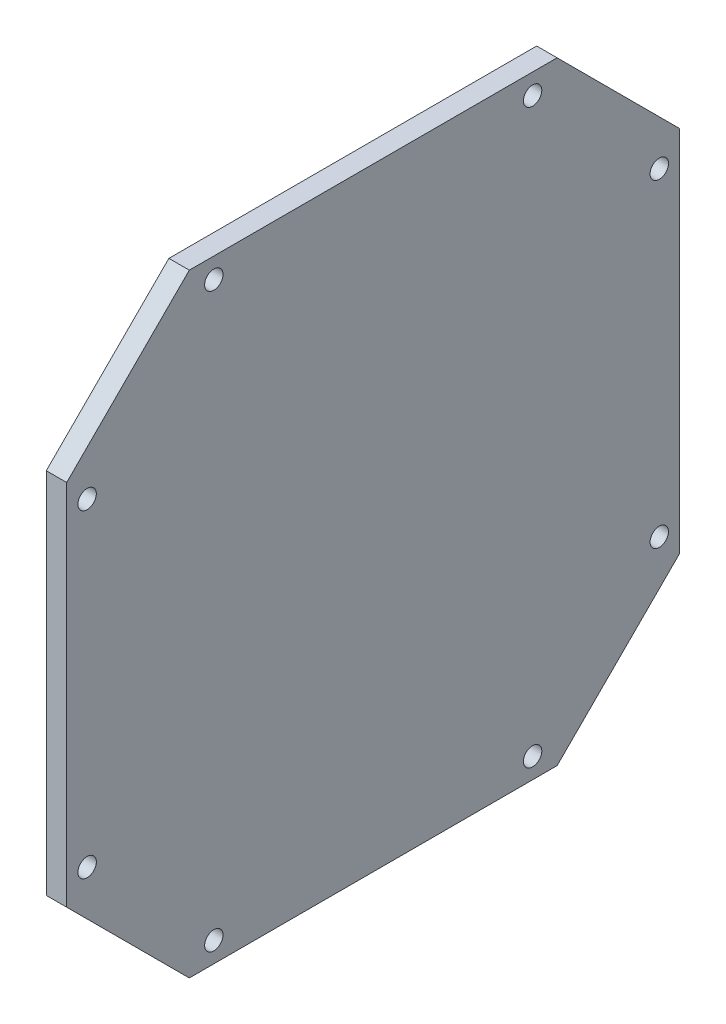
SolidWorks part; units mm, degrees
ref_plane "Front Plane" through (0, 0, 0) normal (1, 0, 0) x (0, 1, 0)
ref_plane "Top Plane" through (0, 0, 0) normal (0, 0, 1) x (0, 1, 0)
ref_plane "Right Plane" through (0, 0, 0) normal (0, 1, 0) x (-1, 0, 0)
sketch "Sketch2" plane through (0, 0, 0) normal (1, 0, 0) x (0, 1, 0)
  line L0 (-150, 90) -> (-90, 150)
  line L1 (-90, 150) -> (90, 150)
  line L2 (-150, 90) -> (-150, -90)
  line L3 (-90, -150) -> (90, -150)
  line L4 (150, 90) -> (150, -90)
  line L5 (-150, 150) -> (150, -150) construction
  line L6 (-150, -150) -> (150, 150) construction
  line L7 (90, 150) -> (150, 90)
  line L8 (90, -150) -> (150, -90)
  line L9 (-150, -90) -> (-90, -150)
  line L10 (55, 0) -> (-55, 0) construction
  line L11 (0, -55) -> (0, 55) construction
  circle A0 centre (-140, 78) radius 4.5
  circle A1 centre (-78, 140) radius 4.5
  circle A2 centre (-78, -140) radius 4.5
  circle A3 centre (-140, -78) radius 4.5
  circle A4 centre (78, -140) radius 4.5
  circle A5 centre (140, -78) radius 4.5
  circle A6 centre (140, 78) radius 4.5
  circle A7 centre (78, 140) radius 4.5
  point P0 (0, 0)
  point P18 (0, 0)
  dimension "D3" = 9
  dimension "D1" = 300
  dimension "D2" = 300
  dimension "D4" = 10
  dimension "D5" = 72
  dimension "D10" = 10
  dimension "D11" = 72
extrude "Boss-Extrude1" add sketch "Sketch2" along normal blind 10
